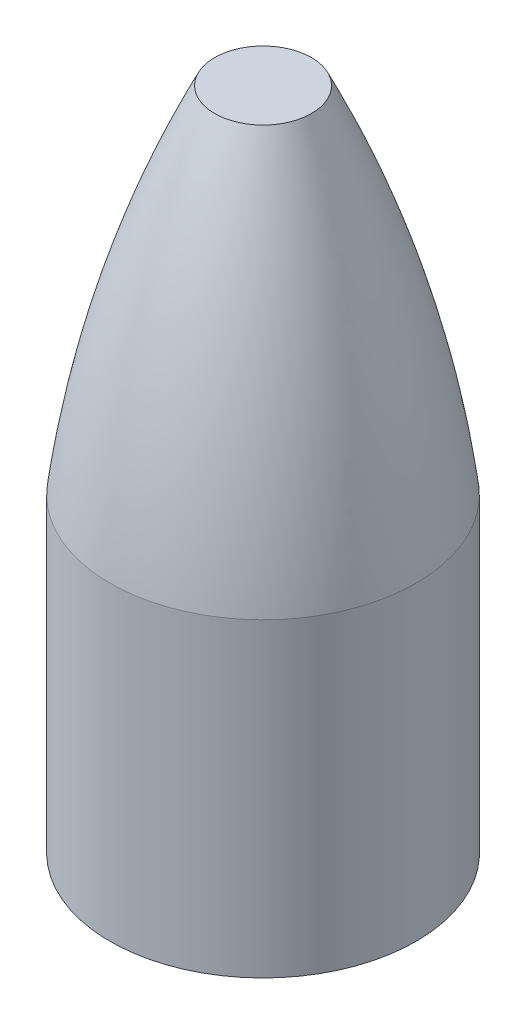
SolidWorks part; units mm, degrees
ref_plane "Front Plane" through (0, 0, 0) normal (0, 0, 1) x (1, 0, 0)
ref_plane "Top Plane" through (0, 0, 0) normal (0, 1, 0) x (1, 0, 0)
ref_plane "Right Plane" through (0, 0, 0) normal (1, 0, 0) x (0, 0, -1)
sketch "Sketch1" plane through (0, 0, 0) normal (0, 0, 1) x (1, 0, 0)
  line L0 (0, 0) -> (0, 9930.13) construction
  line L1 (0, 0) -> (-2286, 0)
  line L2 (0, 0) -> (0, 9930.13)
  line L4 (-2286, 0) -> (-2286, 4634.23)
  line L5 (0, 9930.13) -> (-723.9, 9930.13)
  spline S0 degree 3 poles (-723.9, 9930.13) (-1132.1918, 9076.7964) (-1796.4023, 7345.1508) (-2174.4725, 5529.8238) (-2286, 4634.23) knots 0 0 0 0 0.51178 1 1 1 1
  point P8 (0, 9800.1015)
  dimension "D1" = 2286
  dimension "D2" = 4634.23
  dimension "D3" = 9930.13
  dimension "D4" = 723.9
  dimension "D5" = 5958.332
  dimension "D6" = 7282.434
  dimension "D7" = 8606.282
  dimension "D8" = 2066.798
  dimension "D9" = 1737.106
  dimension "D10" = 1292.098
revolve "Revolve1" add sketch "Sketch1" angle 360 about L0
shell "Shell1" thickness 6.35
